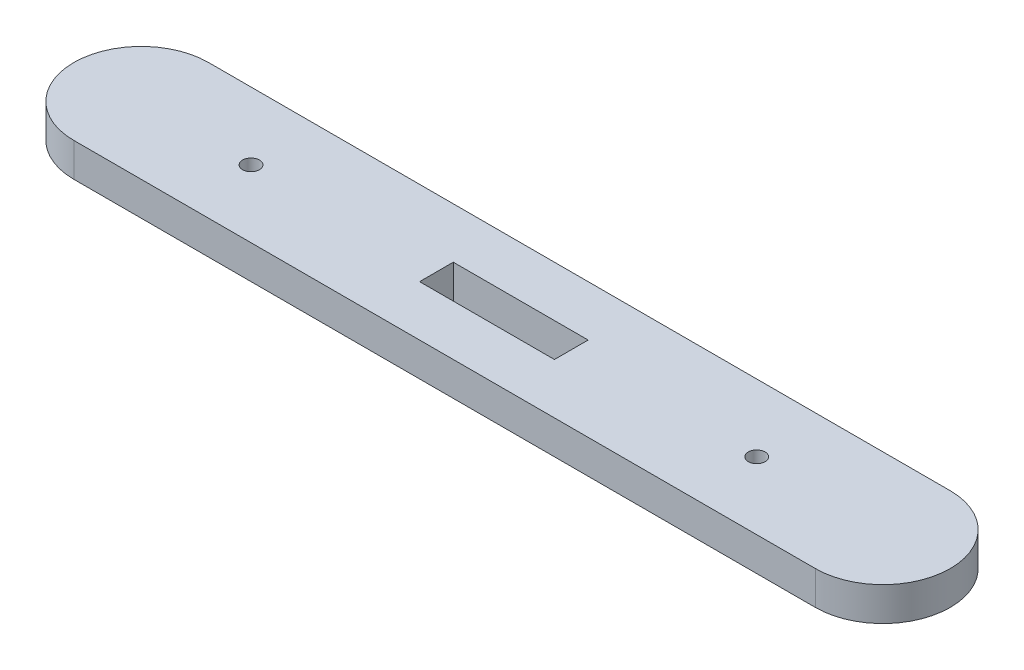
SolidWorks part; units mm, degrees
material "6061 Alloy"
ref_plane "Front Plane" through (0, 0, 0) normal (0, 0, 1) x (1, 0, 0)
ref_plane "Top Plane" through (0, 0, 0) normal (0, 1, 0) x (1, 0, 0)
ref_plane "Right Plane" through (0, 0, 0) normal (1, 0, 0) x (0, 0, -1)
sketch "Sketch1" plane through (0, 0, 0) normal (0, 1, 0) x (1, 0, 0)
  line L0 (72.3352, -24.126) -> (-67.3648, -24.126)
  line L1 (-67.3648, -49.526) -> (72.3352, -49.526)
  line L2 (-11.7474, -33.651) -> (13.6526, -33.651)
  line L3 (13.6526, -33.651) -> (13.6526, -40.001)
  line L4 (-11.7474, -33.651) -> (-11.7474, -40.001)
  line L5 (-11.7474, -40.001) -> (13.6526, -40.001)
  circle A0 centre (-46.6724, -36.826) radius 1.5875
  circle A1 centre (48.5776, -36.826) radius 1.5875
  arc A2 (72.3352, -49.526) -> (72.3352, -24.126) centre (72.3352, -36.826) ccw
  arc A3 (-67.3648, -24.126) -> (-67.3648, -49.526) centre (-67.3648, -36.826) ccw
extrude "Boss-Extrude1" add sketch "Sketch1" along normal blind 6.35
